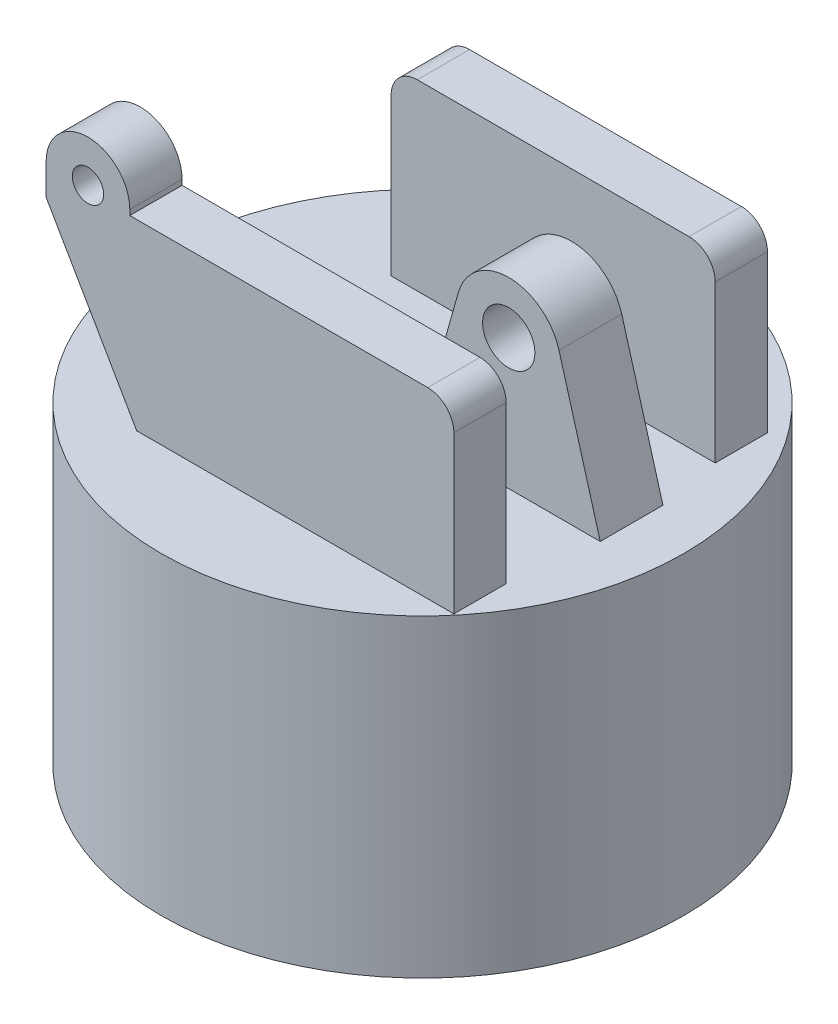
SolidWorks part; units mm, degrees
ref_plane "前视基准面" through (0, 0, 0) normal (0, 0, 1) x (1, 0, 0)
ref_plane "上视基准面" through (0, 0, 0) normal (0, 1, 0) x (1, 0, 0)
ref_plane "右视基准面" through (0, 0, 0) normal (1, 0, 0) x (0, 0, -1)
sketch "草图1" plane through (0, 0, 0) normal (0, 1, 0) x (1, 0, 0)
  circle A0 centre (0, 0) radius 50
  dimension "D1" = 100
extrude "凸台-拉伸1" add sketch "草图1" along normal blind 60
sketch "草图2" plane through (0, 0, 0) normal (0, 0, 1) x (1, 0, 0)
  line L0 (38, 60) -> (38, 95)
  line L1 (50, 60) -> (-50, 60) construction
  line L2 (38, 95) -> (-24, 95)
  line L3 (-24, 95) -> (-24, 96)
  line L4 (-40, 96) -> (-40, 90)
  line L5 (-40, 90) -> (-22.6795, 60)
  line L6 (-22.6795, 60) -> (38, 60)
  arc A0 (-24, 96) -> (-40, 96) centre (-32, 96) ccw
  circle A1 centre (-32, 96) radius 3
  dimension "D2" = 6
  dimension "D3" = 8
  dimension "D4" = 1
  dimension "D1" = 35
  dimension "D5" = 150
  dimension "D6" = 38
  dimension "D7" = 78
  dimension "D8" = 30
extrude "凸台-拉伸2" add sketch "草图2" along normal blind 10 from offset 22
sketch "草图3" plane through (0, 0, 0) normal (0, 0, 1) x (1, 0, 0)
  line L0 (50, 60) -> (-50, 60) construction
  line L1 (38, 95) -> (-24, 95)
  line L2 (38, 95) -> (38, 60)
  line L3 (38, 60) -> (-24, 60)
  line L4 (-24, 95) -> (-24, 60)
extrude "凸台-拉伸3" add sketch "草图3" against normal blind 10 from offset 18 offset against normal yes
fillet "圆角1" radius 5 3 edges at (-24, 95, -23) (38, 95, -23) (38, 95, 27)
sketch "草图4" plane through (0, 0, 0) normal (0, 0, 1) x (1, 0, 0)
  line L0 (12.8808, 87.7334) -> (5, 60)
  line L1 (50, 60) -> (-50, 60) construction
  line L2 (5, 60) -> (40, 60)
  line L3 (40, 60) -> (32.1192, 87.7334)
  line L4 (22.5, 85) -> (22.5, 60) construction
  circle A0 centre (22.5, 85) radius 5
  arc A1 (32.1192, 87.7334) -> (12.8808, 87.7334) centre (22.5, 85) ccw
  dimension "D1" = 10
  dimension "D2" = 20
  dimension "D3" = 35
  dimension "D4" = 40
  dimension "D5" = 25
extrude "凸台-拉伸4" add sketch "草图4" along normal mid plane 12
